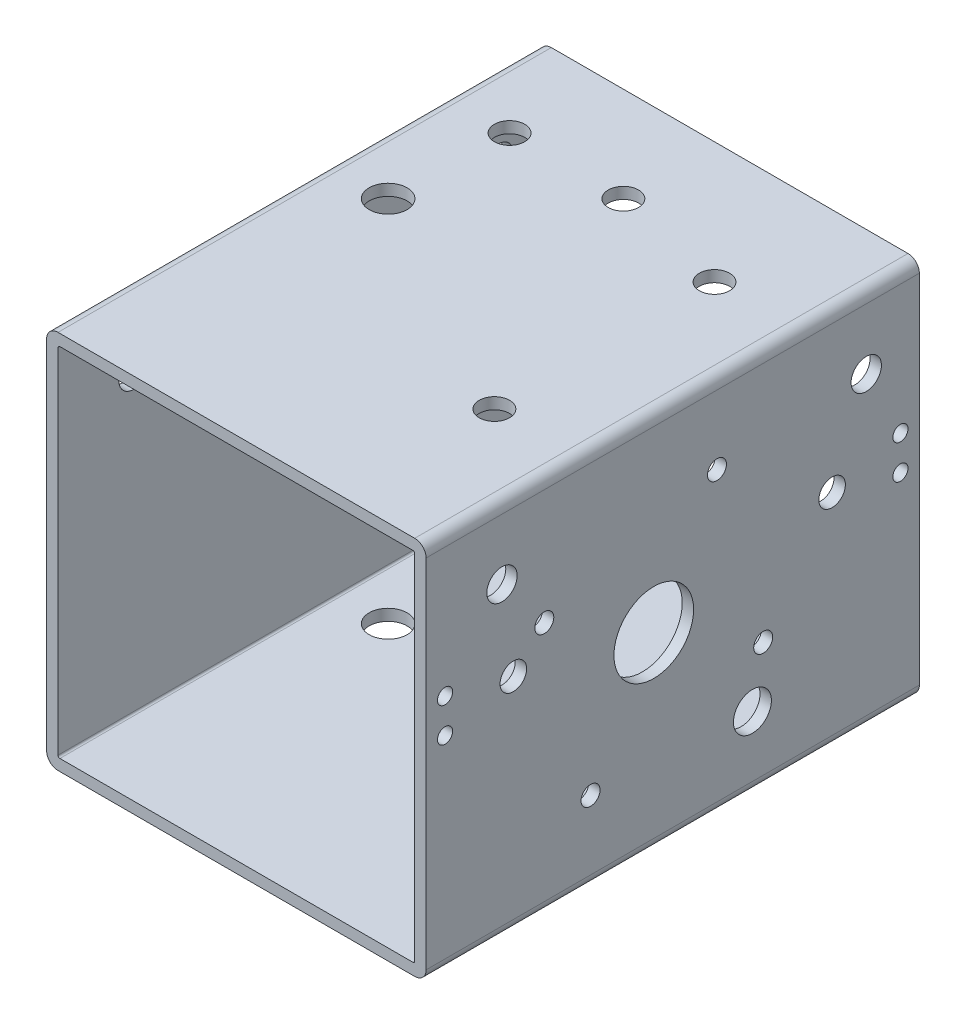
SolidWorks part; units mm, degrees
ref_plane "Front Plane" through (0, 0, 0) normal (0, 0, 1) x (1, 0, 0)
ref_plane "Top Plane" through (0, 0, 0) normal (0, 1, 0) x (1, 0, 0)
ref_plane "Right Plane" through (0, 0, 0) normal (1, 0, 0) x (0, 0, -1)
sketch "Sketch1" plane through (0, 0, 0) normal (0, 0, 1) x (1, 0, 0)
  line L1 (-50, 50) -> (50, 50)
  line L2 (-50, 50) -> (-50, -50)
  line L3 (-50, -50) -> (50, -50)
  line L4 (50, 50) -> (50, -50)
  line L5 (-50, 50) -> (50, -50) construction
  line L6 (-50, -50) -> (50, 50) construction
  point P0 (0, 0)
  dimension "D1" = 100
  dimension "D2" = 100
extrude "Extrude-Thin1" add sketch "Sketch1" along normal blind 130 thin
fillet "Fillet1" radius 0.5 4 edges at (-47, -47, 65) (-47, 47, 65) (47, 47, 65) (47, -47, 65)
fillet "Fillet2" radius 3 4 edges at (50, -50, 65) (-50, -50, 65) (50, 50, 65) (-50, 50, 65)
sketch "Holes - top" plane through (0, 0, 0) normal (0, 1, 0) x (1, 0, 0)
  line L0 (-3, 0) -> (-3, -130) construction
  line L1 (47, -130) -> (-47, -130) construction
  line L2 (-23, 0) -> (-23, -130) construction
  line L3 (47, 0) -> (-47, 0) construction
  line L4 (17, 0) -> (17, -130) construction
  circle A0 centre (-34, -56) radius 11 construction
  circle A1 centre (28, -90) radius 11 construction
  circle A2 centre (28, -32) radius 11 construction
  dimension "D4" = 22
  dimension "D1" = 40
  dimension "D2" = 40
  dimension "D3" = 32
  dimension "D5" = 56
  dimension "D6" = 3
hole_wizard "Ø8.0 (8) Diameter Hole2" positions "Sketch6" profile "Sketch5" hole size "Ø8.0" standard "ANSI Metric" end condition through all
sketch "Sketch6" plane through (0, 50, 0) normal (0, 1, 0) x (1, 0, 0)
  point P0 (28, -32)
  point P6 (28, -90)
sketch "Sketch5" plane through (28, 50, 32) normal (1, 0, 0) x (0, 0, 1)
  line L0 (0, 0) -> (0, 100)
  line L1 (0, 100) -> (4, 100)
  line L2 (4, 100) -> (4, 0)
  line L5 (4, 0) -> (0, 0)
  line L11 (0, -6.35) -> (0, 107.95) construction
  dimension "Thru Hole Dia." = 8
  dimension "Thru Hole Depth" = 100
sketch "Holes - side" plane through (0, 0, 0) normal (1, 0, 0) x (0, 0, -1)
  line L0 (0, 0) -> (-130, 0) construction
  line L1 (-130, -47) -> (-130, 47) construction
  line L2 (-130, 20) -> (0, 20) construction
  line L3 (0, -47) -> (0, 47) construction
  line L4 (-130, -20) -> (0, -20) construction
  circle A0 centre (-110, 31) radius 11 construction
  circle A1 centre (-14, 31) radius 11 construction
  circle A2 centre (-44, -31) radius 11 construction
  dimension "D1" = 40
  dimension "D2" = 22
  dimension "D3" = 20
  dimension "D4" = 14
  dimension "D5" = 44
hole_wizard "Ø8.0 (8) Diameter Hole3" positions "Sketch9" profile "Sketch8" hole size "Ø8.0" standard "ANSI Metric" end condition through all
sketch "Sketch9" plane through (50, 0, 0) normal (1, 0, 0) x (0, 0, -1)
  point P0 (-14, 31)
  point P3 (-110, 31)
sketch "Sketch8" plane through (50, 31, 14) normal (0, 1, 0) x (0, 0, -1)
  line L0 (0, 0) -> (0, 100)
  line L1 (0, 100) -> (4, 100)
  line L2 (4, 100) -> (4, 0)
  line L5 (4, 0) -> (0, 0)
  line L11 (0, -6.35) -> (0, 107.95) construction
  dimension "Thru Hole Dia." = 8
  dimension "Thru Hole Depth" = 100
hole_wizard "Ø10.0 (10) Diameter Hole1" positions "Sketch12" profile "Sketch11" hole size "Ø10.0" standard "ANSI Metric" end condition through all
sketch "Sketch12" plane through (0, 50, 0) normal (0, 1, 0) x (1, 0, 0)
  point P0 (-34, -56)
sketch "Sketch11" plane through (-34, 50, 56) normal (1, 0, 0) x (0, 0, 1)
  line L0 (0, 0) -> (0, 100)
  line L1 (0, 100) -> (5, 100)
  line L2 (5, 100) -> (5, 0)
  line L5 (5, 0) -> (0, 0)
  line L11 (0, -6.35) -> (0, 107.95) construction
  dimension "Thru Hole Dia." = 10
  dimension "Thru Hole Depth" = 100
hole_wizard "Ø10.0 (10) Diameter Hole2" positions "Sketch14" profile "Sketch13" hole size "Ø10.0" standard "ANSI Metric" end condition through all
sketch "Sketch14" plane through (50, 0, 0) normal (1, 0, 0) x (0, 0, -1)
  point P0 (-44, -31)
sketch "Sketch13" plane through (50, -31, 44) normal (0, 1, 0) x (0, 0, -1)
  line L0 (0, 0) -> (0, 100)
  line L1 (0, 100) -> (5, 100)
  line L2 (5, 100) -> (5, 0)
  line L5 (5, 0) -> (0, 0)
  line L11 (0, -6.35) -> (0, 107.95) construction
  dimension "Thru Hole Dia." = 10
  dimension "Thru Hole Depth" = 100
hole_wizard "Ø6.0 (6) Diameter Hole1" positions "Sketch18" profile "Sketch17" hole size "Ø6.0" standard "ANSI Metric"
sketch "Sketch18" plane through (-50, 0, 0) normal (-1, 0, 0) x (0, 0, 1)
  line L0 (56, 35) -> (56, -15) construction
  point P0 (56, -15)
  point P2 (56, 35)
  dimension "D1" = 56
  dimension "D2" = 35
  dimension "D3" = 15
sketch "Sketch17" plane through (-50, -15, 56) normal (0, 1, 0) x (0, 0, 1)
  line L0 (0, 0) -> (0, 3)
  line L1 (0, 3) -> (3, 3)
  line L2 (3, 3) -> (3, 0)
  line L5 (3, 0) -> (0, 0)
  line L11 (0, -6.35) -> (0, 107.95) construction
  dimension "Thru Hole Dia." = 6
  dimension "Thru Hole Depth" = 3
hole_wizard "Ø6.0 (6) Diameter Hole2" positions "Sketch21" profile "Sketch20" hole size "Ø6.0" standard "ANSI Metric"
sketch "Sketch21" plane through (0, -50, 0) normal (0, -1, 0) x (-1, 0, 0)
  line L0 (20, -44) -> (-35, -44) construction
  point P0 (20, -44)
  point P2 (-35, -44)
  dimension "D1" = 44
  dimension "D2" = 35
  dimension "D3" = 20
sketch "Sketch20" plane through (-20, -50, 44) normal (1, 0, 0) x (0, 0, -1)
  line L0 (0, 0) -> (0, 3)
  line L1 (0, 3) -> (3, 3)
  line L2 (3, 3) -> (3, 0)
  line L5 (3, 0) -> (0, 0)
  line L11 (0, -6.35) -> (0, 107.95) construction
  dimension "Thru Hole Dia." = 6
  dimension "Thru Hole Depth" = 3
sketch "Holes - Nema 23 motor" plane through (0, 0, 0) normal (1, 0, 0) x (0, 0, -1)
  line L0 (-98.8427, 16.6524) -> (-53.3476, 28.8427) construction
  line L1 (-98.8427, 16.6524) -> (-86.6524, -28.8427) construction
  line L2 (-53.3476, 28.8427) -> (-41.1573, -16.6524) construction
  line L3 (-86.6524, -28.8427) -> (-41.1573, -16.6524) construction
  line L4 (-98.8427, 16.6524) -> (-41.1573, -16.6524) construction
  line L5 (-53.3476, 28.8427) -> (-86.6524, -28.8427) construction
  line L6 (0, 0) -> (-130, 0) construction
  point P1 (-70, 0)
  dimension "D1" = 70
  dimension "D2" = 47.1
  dimension "D3" = 47.1
  dimension "D4" = 15
hole_wizard "Ø21.0 (21) Diameter Hole1" positions "Sketch24" profile "Sketch23" hole size "Ø21.0" standard "ANSI Metric"
sketch "Sketch24" plane through (50, 0, 0) normal (1, 0, 0) x (0, 0, -1)
  point P0 (-70, 0)
sketch "Sketch23" plane through (50, 0, 70) normal (0, 1, 0) x (0, 0, -1)
  line L0 (0, 0) -> (0, 3)
  line L1 (0, 3) -> (10.5, 3)
  line L2 (10.5, 3) -> (10.5, 0)
  line L5 (10.5, 0) -> (0, 0)
  line L11 (0, -6.35) -> (0, 107.95) construction
  dimension "Thru Hole Dia." = 21
  dimension "Thru Hole Depth" = 3
hole_wizard "Ø5.0 (5) Diameter Hole1" positions "Sketch26" profile "Sketch25" hole size "Ø5.0" standard "ANSI Metric"
sketch "Sketch26" plane through (50, 0, 0) normal (1, 0, 0) x (0, 0, -1)
  point P0 (-41.1573, -16.6524)
  point P3 (-53.3476, 28.8427)
  point P6 (-98.8427, 16.6524)
  point P9 (-86.6524, -28.8427)
sketch "Sketch25" plane through (50, -16.6524, 41.1573) normal (0, 1, 0) x (0, 0, -1)
  line L0 (0, 0) -> (0, 3)
  line L1 (0, 3) -> (2.5, 3)
  line L2 (2.5, 3) -> (2.5, 0)
  line L5 (2.5, 0) -> (0, 0)
  line L11 (0, -6.35) -> (0, 107.95) construction
  dimension "Thru Hole Dia." = 5
  dimension "Thru Hole Depth" = 3
hole_wizard "Ø8.0 (8) Diameter Hole4" positions "Sketch29" profile "Sketch28" hole size "Ø8.0" standard "ANSI Metric"
sketch "Sketch29" plane through (0, 50, 0) normal (0, 1, 0) x (1, 0, 0)
  line L0 (-3, 0) -> (-3, -130) construction
  point P0 (-3, -25)
  dimension "D2" = 7
sketch "Sketch28" plane through (-3, 50, 25) normal (1, 0, 0) x (0, 0, 1)
  line L0 (0, 0) -> (0, 3)
  line L1 (0, 3) -> (4, 3)
  line L2 (4, 3) -> (4, 0)
  line L5 (4, 0) -> (0, 0)
  line L11 (0, -6.35) -> (0, 107.95) construction
  dimension "Thru Hole Dia." = 8
  dimension "Thru Hole Depth" = 3
sketch "Sketch31" plane through (50, 0, 0) normal (1, 0, 0) x (0, 0, -1)
  line L0 (0, -47) -> (0, 47) construction
  line L1 (-130, 50) -> (0, 50) construction
  line L2 (-65, 117.0212) -> (-65, -118.5233) construction
  line L3 (-130, -47) -> (-130, 47) construction
  circle A0 centre (-5, 4) radius 2
  circle A1 centre (-5, 13) radius 2
  circle A2 centre (-125, 13) radius 2
  circle A3 centre (-125, 4) radius 2
  circle A4 centre (-23, 8.5) radius 3.5
  circle A5 centre (-107, 8.5) radius 3.5
  dimension "D1" = 4
  dimension "D2" = 4
  dimension "D3" = 9
  dimension "D4" = 5
  dimension "D5" = 46
  dimension "D6" = 5
  dimension "D8" = 7
  dimension "D9" = 18
  dimension "D7" = 65
  dimension "D10" = 4.5
extrude "Cut-Extrude1" cut sketch "Sketch31" against normal up to next
hole_wizard "Ø8.0 (8) Diameter Hole5" positions "Sketch32" profile "Sketch33" hole size "Ø8.0" standard "ANSI Metric"
sketch "Sketch32" plane through (0, 50, 0) normal (0, 1, 0) x (1, 0, 0)
  line L1 (47, 0) -> (-47, 0) construction
  circle A0 centre (-3, -25) radius 4 construction
  point P0 (-33, -25)
  dimension "D1" = 30
  dimension "D2" = 25
sketch "Sketch33" plane through (-33, 50, 25) normal (1, 0, 0) x (0, 0, 1)
  line L0 (0, 0) -> (0, 3)
  line L1 (0, 3) -> (4, 3)
  line L2 (4, 3) -> (4, 0)
  line L5 (4, 0) -> (0, 0)
  line L11 (0, -6.35) -> (0, 107.95) construction
  dimension "Thru Hole Dia." = 8
  dimension "Thru Hole Depth" = 3
equation "\"L\"= 130"
equation "\"D1@Extrude-Thin1\"=\"L\""
equation "\"d-bearing\"= 22'diameter of bearing"
equation "\"D4@Holes - top\"=\"d-bearing\""
equation "\"D2@Holes - side\"=\"d-bearing\""
